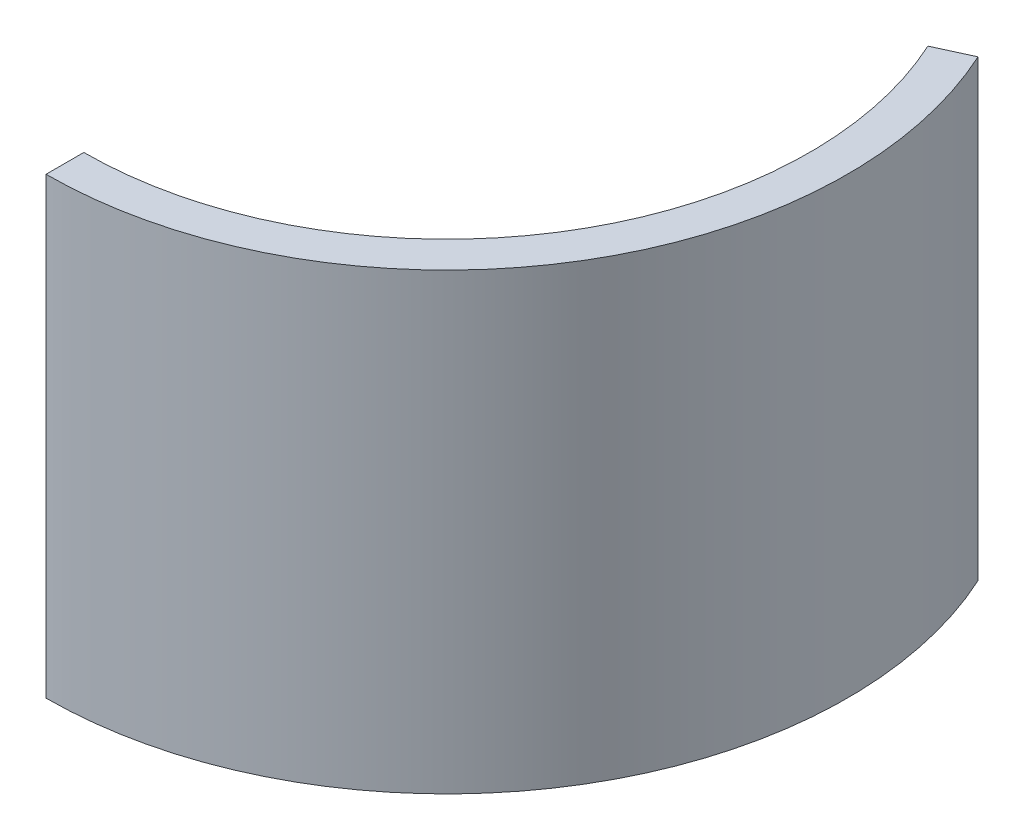
SolidWorks part; units mm, degrees
material "柔性聚氨酯泡沫体"
ref_plane "前视基准面" through (0, 0, 0) normal (0, 0, 1) x (1, 0, 0)
ref_plane "上视基准面" through (0, 0, 0) normal (0, 1, 0) x (1, 0, 0)
ref_plane "右视基准面" through (0, 0, 0) normal (1, 0, 0) x (0, 0, -1)
other "Configuration Table"
sketch "草图1" plane through (0, 0, 0) normal (0, 1, 0) x (1, 0, 0)
  line L0 (21.8174, 10) -> (24.0901, 11.0417)
  line L1 (0, -24) -> (0, -26.5)
  circle A0 centre (0, 0) radius 26.5 construction
  circle A1 centre (0, 0) radius 24 construction
  arc A2 (21.8174, 10) -> (0, -24) centre (0, 0) cw
  arc A3 (0, -26.5) -> (24.0901, 11.0417) centre (0, 0) ccw
  dimension "D1" = 48
  dimension "D2" = 53
  dimension "D3" = 34
extrude "凸台-拉伸1" add sketch "草图1" along normal blind 30 contours L1 A3 L0 A2
